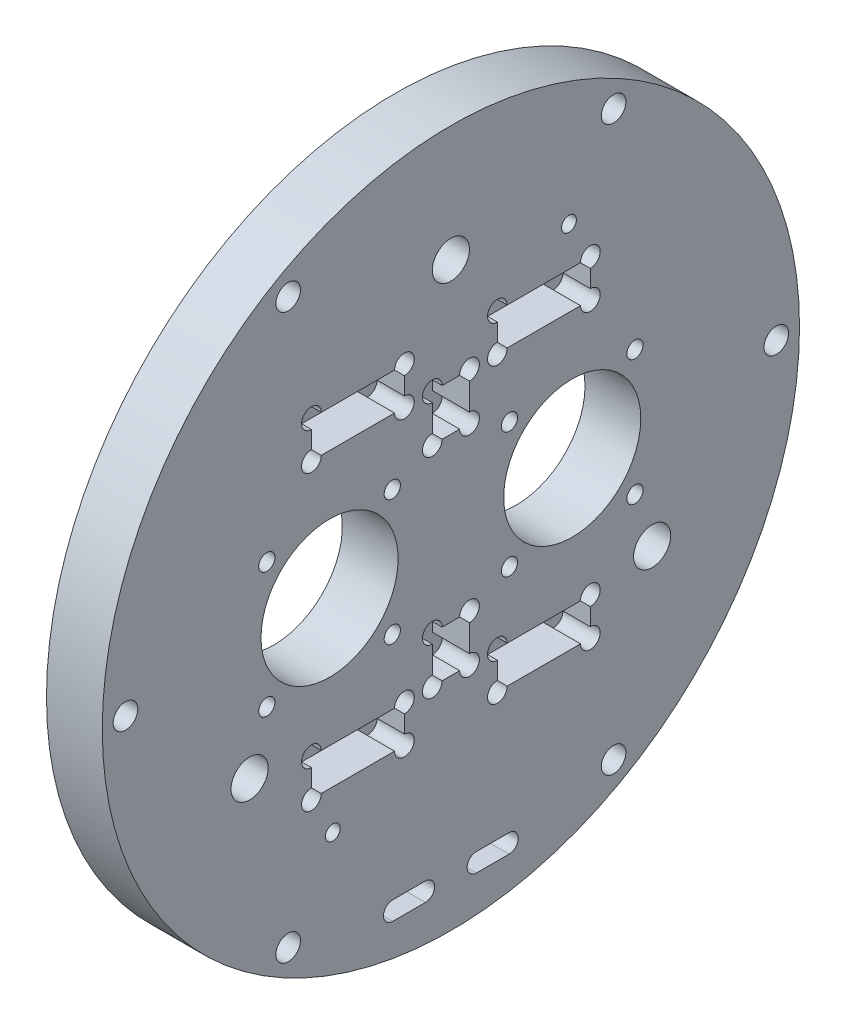
SolidWorks part; units mm, degrees
ref_plane "Front Plane" through (0, 0, 0) normal (0, 0, 1) x (1, 0, 0)
ref_plane "Top Plane" through (0, 0, 0) normal (0, 1, 0) x (1, 0, 0)
ref_plane "Right Plane" through (0, 0, 0) normal (1, 0, 0) x (0, 0, -1)
sketch "Sketch1" plane through (0, 0, 0) normal (1, 0, 0) x (0, 0, -1)
  line L0 (0, -75) -> (0, 75) construction
  line L1 (-75, 0) -> (75, 0) construction
  line L2 (26.1, 0) -> (39.5969, 13.4969) construction
  circle A0 centre (0, 0) radius 75
  circle A1 centre (0, 50) radius 4
  circle A2 centre (43.3013, -25) radius 4
  circle A3 centre (-43.3013, -25) radius 4
  circle A4 centre (26.1, 0) radius 14.75
  circle A5 centre (-26.1, 0) radius 14.75
  circle A6 centre (39.5969, 13.4969) radius 1.75
  circle A7 centre (39.5969, -13.4969) radius 1.75
  circle A8 centre (12.6031, -13.4969) radius 1.75
  circle A9 centre (12.6031, 13.4969) radius 1.75
  circle A10 centre (-39.5969, -13.4969) radius 1.75
  circle A11 centre (-12.6031, -13.4969) radius 1.75
  circle A12 centre (-12.6031, 13.4969) radius 1.75
  circle A13 centre (-39.5969, 13.4969) radius 1.75
  circle A14 centre (26.1, 0) radius 22.1 construction
  circle A15 centre (-26.1, 0) radius 22.1 construction
  point P12 (0, 0)
  point P29 (26.1, 0)
  point P37 (-4, 0)
  point P40 (4, 0)
  dimension "D1" = 150
  dimension "D2" = 8
  dimension "D5" = 29.5
  dimension "D7" = 3.5
  dimension "D11" = 44.2
  dimension "D3" = 50
  dimension "D4" = 3
  dimension "D6" = 8
  dimension "D8" = 19.0875
  dimension "D10" = 45
  dimension "D9" = 4
extrude "Boss-Extrude1" add sketch "Sketch1" along normal blind 12
sketch "Sketch2" plane through (12, 0, 0) normal (1, 0, 0) x (0, 0, -1)
  line L0 (-97.5918, 0) -> (102.3086, 0) construction
  line L1 (0, 96.3466) -> (0, -103.9448) construction
  line L2 (10, -27.5) -> (10, -35.5)
  line L3 (-30, -27.5) -> (-10, -27.5)
  line L4 (-30, -27.5) -> (-30, -35.5)
  line L5 (-30, -35.5) -> (-10, -35.5)
  line L6 (-10, -27.5) -> (-10, -35.5)
  line L7 (30, -27.5) -> (10, -27.5)
  line L8 (30, -27.5) -> (30, -35.5)
  line L9 (30, -35.5) -> (10, -35.5)
  line L10 (-30, 27.5) -> (-30, 35.5)
  line L11 (-30, 35.5) -> (-10, 35.5)
  line L12 (-10, 27.5) -> (-10, 35.5)
  line L13 (-30, 27.5) -> (-10, 27.5)
  line L14 (10, 27.5) -> (10, 35.5)
  line L15 (30, 35.5) -> (10, 35.5)
  line L16 (30, 27.5) -> (10, 27.5)
  line L17 (30, 27.5) -> (30, 35.5)
  line L18 (-4, -17.5) -> (4, -17.5)
  line L19 (-4, 27.5) -> (4, 27.5)
  line L20 (-4, 27.5) -> (-4, 17.5)
  line L21 (-4, 17.5) -> (4, 17.5)
  line L22 (4, 27.5) -> (4, 17.5)
  line L23 (-4, -27.5) -> (-4, -17.5)
  line L24 (-4, -27.5) -> (4, -27.5)
  line L25 (4, -27.5) -> (4, -17.5)
  line L26 (27.8787, -35.5) -> (30, -33.3787) construction
  line L27 (-42.3534, -67) -> (39.6493, -67) construction
  line L28 (-5.5, -67) -> (-5.5, -63)
  line L29 (12.5, -67) -> (5.5, -67)
  line L30 (12.5, -67) -> (12.5, -63)
  line L31 (12.5, -63) -> (5.5, -63)
  line L32 (5.5, -67) -> (5.5, -63)
  line L33 (-12.5, -63) -> (-5.5, -63)
  line L34 (-12.5, -67) -> (-12.5, -63)
  line L35 (-12.5, -67) -> (-5.5, -67)
  circle A0 centre (30, -35.5) radius 2.1213 construction
  circle A1 centre (0, 0) radius 75 construction
  point P23 (0, 27.5)
  point P31 (30, -33.3787)
  point P32 (0, -75)
  point P33 (27.8787, -35.5)
  dimension "D1" = 27.5
  dimension "D2" = 8
  dimension "D3" = 20
  dimension "D4" = 20
  dimension "D5" = 8
  dimension "D6" = 10
  dimension "D7" = 8
  dimension "D8" = 4
  dimension "D9" = 7
  dimension "D10" = 25
extrude "Cut-Extrude1" cut sketch "Sketch2" against normal blind 8
sketch "Sketch3" plane through (0, 0, 0) normal (-1, 0, 0) x (0, 0, 1)
  circle A0 centre (-70, 0) radius 2.65
  circle A1 centre (-35, 60.6218) radius 2.65
  circle A2 centre (35, 60.6218) radius 2.65
  circle A3 centre (70, 0) radius 2.65
  circle A4 centre (35, -60.6218) radius 2.65
  circle A5 centre (-35, -60.6218) radius 2.65
  point P16 (0, 0)
  dimension "D2" = 5.3
  dimension "D1" = 70
  dimension "D3" = 6
extrude "Cut-Extrude2" cut sketch "Sketch3" against normal up to next
sketch "Sketch4" plane through (12, 0, 0) normal (1, 0, 0) x (0, 0, -1)
  line L0 (12.5, -67) -> (12.5, -63) construction
  line L2 (5.5, -63) -> (5.5, -67) construction
  line L3 (-5.5, -67) -> (-5.5, -63) construction
  line L4 (-12.5, -63) -> (-12.5, -67) construction
  circle A0 centre (-10, -35.5) radius 2.1213
  circle A1 centre (-10, -27.5) radius 2.1213
  circle A2 centre (-30, -27.5) radius 2.1213
  circle A3 centre (-30, -35.5) radius 2.1213
  circle A4 centre (12.5, -65) radius 2
  circle A5 centre (5.5, -65) radius 2
  circle A6 centre (-5.5, -65) radius 2
  circle A7 centre (-12.5, -65) radius 2
  circle A12 centre (10, -35.5) radius 2.1213
  circle A13 centre (10, -27.5) radius 2.1213
  circle A14 centre (30, -27.5) radius 2.1213
  circle A15 centre (30, -35.5) radius 2.1213
  circle A16 centre (4, -27.5) radius 2.1213
  circle A17 centre (-4, -27.5) radius 2.1213
  circle A18 centre (-4, -17.5) radius 2.1213
  circle A19 centre (4, -17.5) radius 2.1213
  circle A20 centre (4, 27.5) radius 2.1213
  circle A21 centre (-4, 27.5) radius 2.1213
  circle A22 centre (-4, 17.5) radius 2.1213
  circle A23 centre (4, 17.5) radius 2.1213
  circle A24 centre (10, 27.5) radius 2.1213
  circle A25 centre (10, 35.5) radius 2.1213
  circle A26 centre (30, 35.5) radius 2.1213
  circle A27 centre (30, 27.5) radius 2.1213
  circle A28 centre (-10, 35.5) radius 2.1213
  circle A29 centre (-10, 27.5) radius 2.1213
  circle A30 centre (-30, 27.5) radius 2.1213
  circle A31 centre (-30, 35.5) radius 2.1213
  point P2 (-12.1213, -35.5)
  point P5 (-10, -33.3787)
  dimension "D1" = 3
extrude "Cut-Extrude3" cut sketch "Sketch4" against normal up to surface (8 mm away) up to face at (4, -31.5, 20)
sketch "Sketch5" plane through (0, 0, 0) normal (-1, 0, 0) x (0, 0, 1)
  line L0 (35, -60.6218) -> (-35, 60.6218) construction
  line L1 (0, 113.7201) -> (0, -122.5246) construction
  line L2 (-128.5049, 0) -> (121.7105, 0) construction
  circle A0 centre (35, -60.6218) radius 2.65 construction
  circle A1 centre (25.4034, -44) radius 1.6
  circle A2 centre (-25.4034, 44) radius 1.6
  point P12 (0, 0)
  dimension "D2" = 3.2
  dimension "D1" = 2
  dimension "D3" = 44
  dimension "D4" = 50.8068
extrude "Cut-Extrude4" cut sketch "Sketch5" against normal up to next
